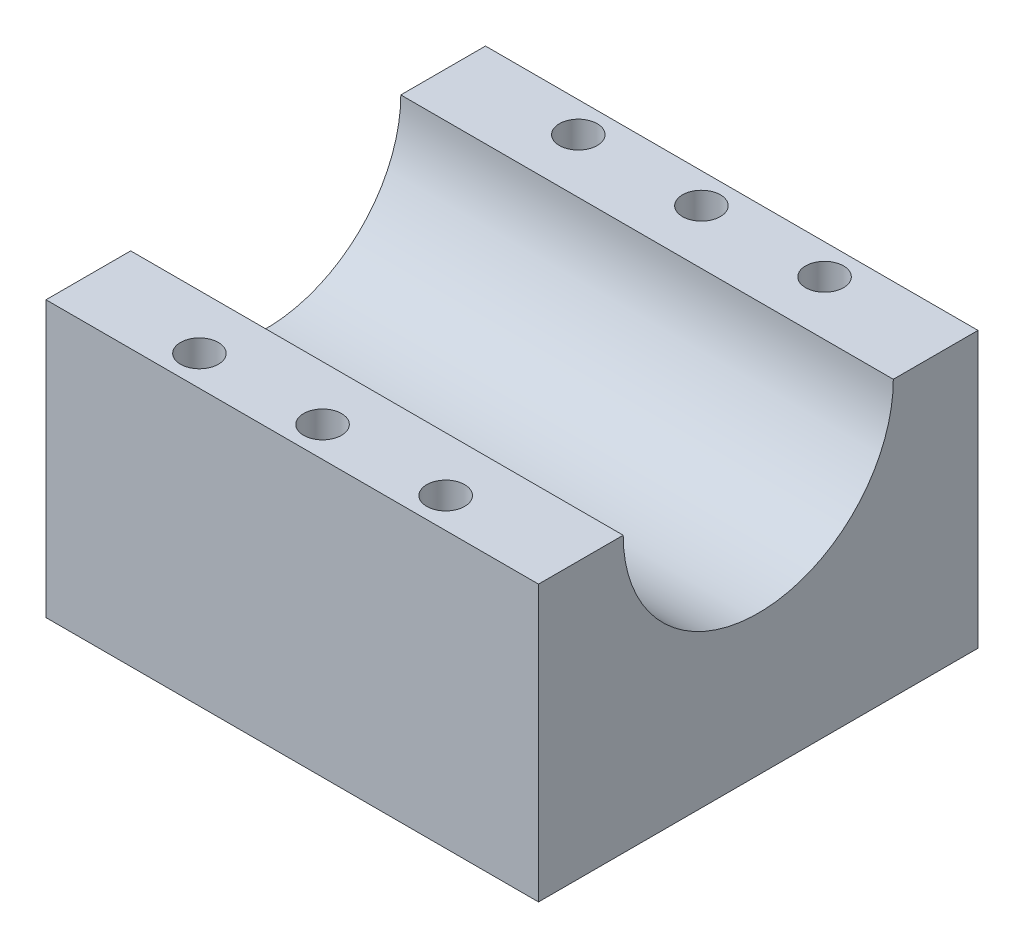
SolidWorks part; units mm, degrees
ref_plane "Front Plane" through (0, 0, 0) normal (0, 0, 1) x (1, 0, 0)
ref_plane "Top Plane" through (0, 0, 0) normal (0, 1, 0) x (1, 0, 0)
ref_plane "Right Plane" through (0, 0, 0) normal (1, 0, 0) x (0, 0, -1)
sketch "Sketch1" plane through (0, 0, 0) normal (0, 1, 0) x (1, 0, 0)
  line L0 (-40.0608, 0) -> (47.511, 0) construction
  line L1 (-32.5, -29) -> (32.5, -29)
  line L2 (-32.5, -29) -> (-32.5, 29)
  line L3 (-32.5, 29) -> (32.5, 29)
  line L4 (32.5, -29) -> (32.5, 29)
  line L5 (-32.5, -29) -> (32.5, 29) construction
  line L6 (-32.5, 29) -> (32.5, -29) construction
  line L7 (-32.5, 25) -> (32.5, 25) construction
  line L8 (-32.5, 18.075) -> (32.5, 18.075) construction
  line L9 (-32.5, -25) -> (32.5, -25) construction
  line L10 (-32.5, -18.075) -> (32.5, -18.075) construction
  line L11 (0, -29) -> (0, 29) construction
  circle A0 centre (-16.25, 25) radius 2.5
  circle A1 centre (16.25, 25) radius 2.5
  circle A2 centre (16.25, -25) radius 2.5
  circle A3 centre (-16.25, -25) radius 2.5
  circle A4 centre (0, 25) radius 2.5
  circle A5 centre (0, -25) radius 2.5
  point P0 (0, 0)
  dimension "D3" = 5
  dimension "D4" = 5
  dimension "D9" = 5
  dimension "D10" = 5
  dimension "D1" = 65
  dimension "D2" = 58
  dimension "D5" = 16.25
  dimension "16.25" = 16.25
  dimension "D7" = 18.075
  dimension "D8" = 4
extrude "Boss-Extrude1" add sketch "Sketch1" along normal blind 36.33
sketch "Sketch2" plane through (32.5, 0, 0) normal (1, 0, 0) x (0, 0, -1)
  line L0 (-29, 36.33) -> (29, 36.33) construction
  circle A0 centre (0, 36.33) radius 17.825
  dimension "D2" = 35.65
  dimension "D1" = 0
extrude "Cut-Extrude1" cut sketch "Sketch2" against normal through all
sketch "Sketch3" plane through (32.5, 0, 0) normal (1, 0, 0) x (0, 0, -1)
  line L1 (-29, 0) -> (29, 0)
  line L2 (-29, 0) -> (-29, 36.33)
  line L3 (-29, 36.33) -> (29, 36.33)
  line L4 (29, 0) -> (29, 36.33)
